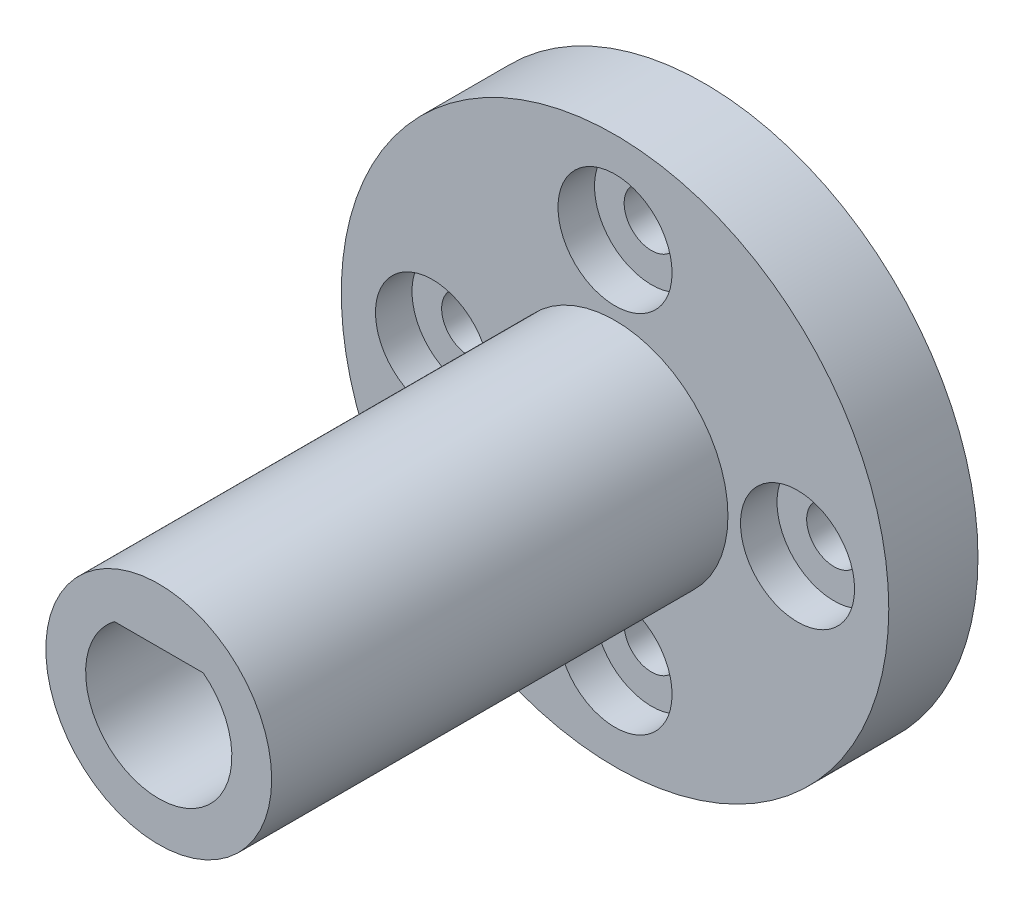
SolidWorks part; units mm, degrees
ref_plane "Plan de face" through (0, 0, 0) normal (0, 0, 1) x (1, 0, 0)
ref_plane "Plan de dessus" through (0, 0, 0) normal (0, 1, 0) x (1, 0, 0)
ref_plane "Plan de droite" through (0, 0, 0) normal (1, 0, 0) x (0, 0, -1)
sketch "Esquisse1" plane through (0, 0, 0) normal (0, 0, 1) x (1, 0, 0)
  circle A0 centre (0, 0) radius 12
  dimension "D1" = 24
extrude "Boss.-Extru.1" add sketch "Esquisse1" along normal blind 3.91
sketch "Esquisse6" plane through (0, 0, 0) normal (0, 0, -1) x (-1, 0, 0)
  circle A0 centre (0, 0) radius 4
  dimension "D1" = 8
extrude "Enlèv. mat.-Extru.2" cut sketch "Esquisse6" against normal blind 1.91
sketch "Esquisse7" plane through (0, 0, 3.91) normal (0, 0, 1) x (1, 0, 0)
  line L0 (1.9481, 2.545) -> (-1.9481, 2.545)
  line L1 (-5.4714, -3.205) -> (6.192, -3.205) construction
  arc A0 (-1.9481, 2.545) -> (1.9481, 2.545) centre (0, 0) ccw
  circle A1 centre (0, 0) radius 4.95
  dimension "D1" = 6.41
  dimension "D3" = 9.9
  dimension "D2" = 5.75
extrude "Boss.-Extru.2" add sketch "Esquisse7" along normal blind 20 contours A1 L1 A0 L0 | L1 A1
hole_wizard "Chambrage pour vis à tête ronde bombée M21" positions "Esquisse10" profile "Esquisse11" counterbore size "M2" standard "Ansi Metric" end condition through all
sketch "Esquisse10" plane through (0, 0, 3.91) normal (0, 0, 1) x (1, 0, 0)
  point P0 (0, 8)
  dimension "D1" = 8
sketch "Esquisse11" plane through (0, 8, 3.91) normal (1, 0, 0) x (0, -1, 0)
  line L0 (0, 0) -> (0, 3.91)
  line L1 (0, 3.91) -> (1.2, 3.91)
  line L3 (1.2, 3.91) -> (1.2, 1.6)
  line L4 (1.2, 1.6) -> (2.5, 1.6)
  line L5 (2.5, 1.6) -> (2.5, 0)
  line L7 (2.5, 0) -> (0, 0)
  line L11 (0, -6.35) -> (0, 107.95) construction
  dimension "Diamètre du perçage jusqu'au prochain" = 2.4
  dimension "Profondeur du perçage jusqu'au prochain" = 3.91
  dimension "Diamètre du chambrage" = 5
  dimension "Profondeur du chambrage" = 1.6
pattern_circular "Répétition circulaire2" count 4 every 90 about axis through (0, 0, 0) along (0, 0, 1) of "Chambrage pour vis à tête ronde bombée M21"
